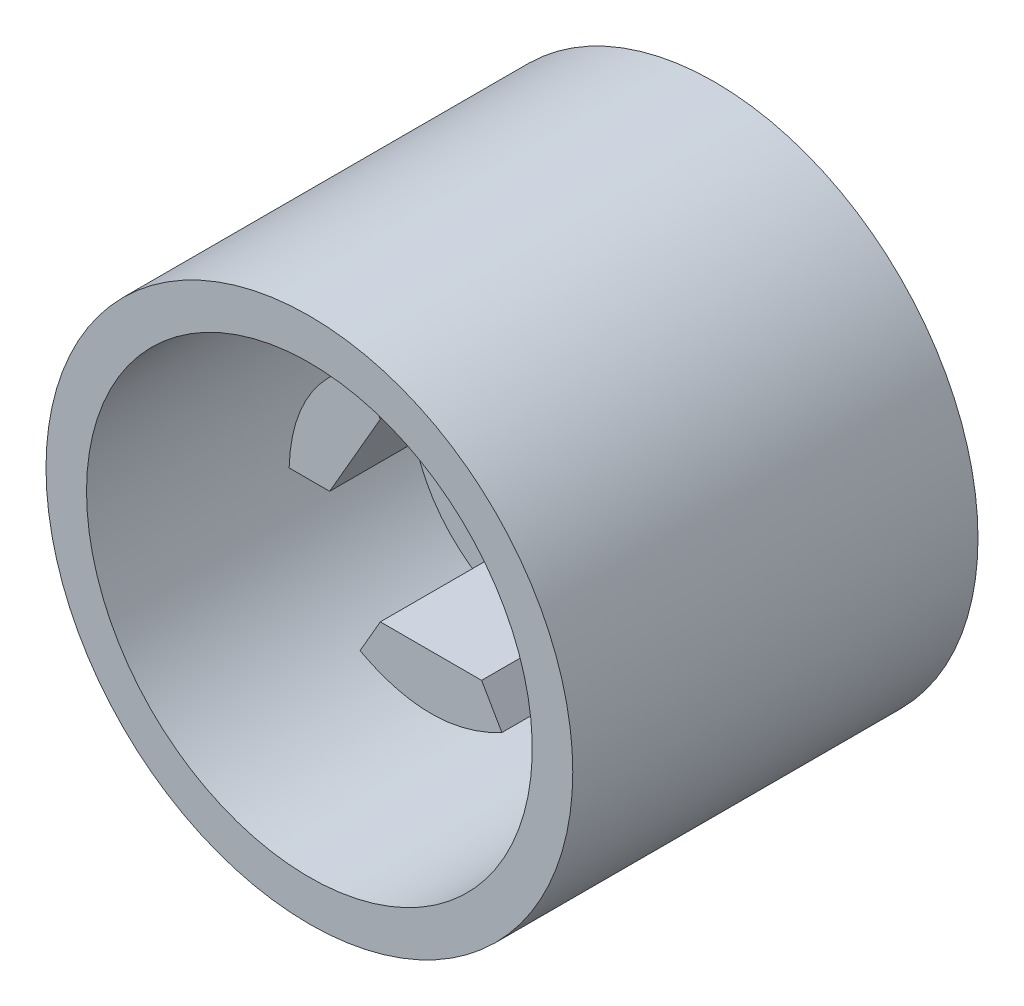
SolidWorks part; units mm, degrees
ref_plane "Front Plane" through (0, 0, 0) normal (0, 0, 1) x (1, 0, 0)
ref_plane "Top Plane" through (0, 0, 0) normal (0, 1, 0) x (1, 0, 0)
ref_plane "Right Plane" through (0, 0, 0) normal (1, 0, 0) x (0, 0, -1)
sketch "Sketch1" plane through (0, 0, 0) normal (0, 1, 0) x (1, 0, 0)
  line L0 (-4.8418, 12.6364) -> (-4.8418, 11.0489)
  line L1 (-4.8418, 12.6364) -> (5.477, 12.6364)
  line L2 (-4.8418, 12.6364) -> (-4.8418, -3.2386)
  line L3 (-4.8418, -3.2386) -> (5.477, -3.2386)
  line L4 (5.477, 12.6364) -> (5.477, -3.2386)
  line L5 (-4.8418, 11.0489) -> (-0.873, 11.0489)
  line L7 (5.477, 12.6364) -> (3.8895, 12.6364)
  line L9 (-0.873, 11.0489) -> (-0.873, 6.2864)
  line L10 (-0.873, 6.2864) -> (0.7145, 6.2864)
  line L11 (0.7145, 11.0489) -> (0.7145, 6.2864)
  line L12 (0.7145, 11.0489) -> (3.8895, 11.0489)
  line L13 (3.8895, 11.0489) -> (3.8895, -3.2386)
  dimension "D1" = 10.3187
  dimension "D2" = 15.875
  dimension "D3" = 1.5875
  dimension "D4" = 3.9688
  dimension "D5" = 1.5875
  dimension "D7" = 1.5875
revolve "Revolve1" add sketch "Sketch1" angle 360 about L2
sketch "Sketch3" plane through (0, 0, -11.0489) normal (0, 0, 1) x (1, 0, 0)
  line L1 (-0.873, 0) -> (-2.8574, 3.437)
  line L2 (-2.8574, 3.437) -> (-6.8262, 3.437)
  line L3 (-6.8262, 3.437) -> (-8.8105, 0)
  line L4 (-8.8105, 0) -> (-6.8262, -3.437)
  line L5 (-6.8262, -3.437) -> (-2.8574, -3.437)
  line L6 (-2.8574, -3.437) -> (-0.873, 0)
  circle A0 centre (-4.8418, 0) radius 3.437 construction
extrude "Extrude-Thin1" add sketch "Sketch3" along normal blind 4.7625 thin
sketch "Sketch4" plane through (0, 0, -6.2864) normal (0, 0, 1) x (1, 0, 0)
  line L0 (-8.8105, 0) -> (-10.398, 0)
  line L1 (-6.8262, 3.437) -> (-7.6199, 4.8119)
  line L2 (-6.8262, 3.437) -> (-8.8105, 0) construction
  line L3 (-6.8262, 3.437) -> (-8.8105, 0) construction
  line L4 (-6.8262, 3.437) -> (-8.8105, 0)
  circle A0 centre (-4.8418, 0) radius 5.5563 construction
  circle A1 centre (-4.8418, 0) radius 5.5563 construction
  spline S0 degree 2 poles (-7.6199, 4.8119) (-10.3011, 3.1454) (-10.398, 0) knots 0 0 0 1 1 1
extrude "Boss-Extrude3" add sketch "Sketch4" along normal blind 4.7625 contours L1 S0 L0 L4
sketch "Sketch6" plane through (0, 0, -6.2864) normal (0, 0, 1) x (1, 0, 0)
  line L0 (-2.8574, 3.437) -> (-2.0637, 4.8119)
  line L2 (-0.873, 0) -> (0.7145, 0)
  line L3 (-2.8574, 3.437) -> (-0.873, 0)
  circle A0 centre (-4.8418, 0) radius 5.5563 construction
  arc A1 (-10.398, 0) -> (-7.6199, 4.8119) centre (-4.8418, 0) ccw construction
  spline S0 degree 2 poles (-2.0637, 4.8119) (0.6187, 3.1433) (0.7145, 0) knots 0 0 0 1 1 1
extrude "Boss-Extrude4" add sketch "Sketch6" along normal blind 4.7625
sketch "Sketch7" plane through (0, 0, -6.2864) normal (0, 0, 1) x (1, 0, 0)
  line L0 (-6.8262, -3.437) -> (-7.6199, -4.8119)
  line L1 (-2.8574, -3.437) -> (-2.0637, -4.8119)
  line L2 (-6.8262, -3.437) -> (-2.8574, -3.437)
  circle A0 centre (-4.8418, 0) radius 5.5563 construction
  arc A1 (-10.398, 0) -> (0.7145, 0) centre (-4.8418, 0) ccw construction
  spline S0 degree 2 poles (-7.6199, -4.8119) (-4.8418, -6.3006) (-2.0637, -4.8119) knots 0 0 0 1 1 1
extrude "Boss-Extrude5" add sketch "Sketch7" along normal blind 4.7625 contours L0 S0 L1 L2
